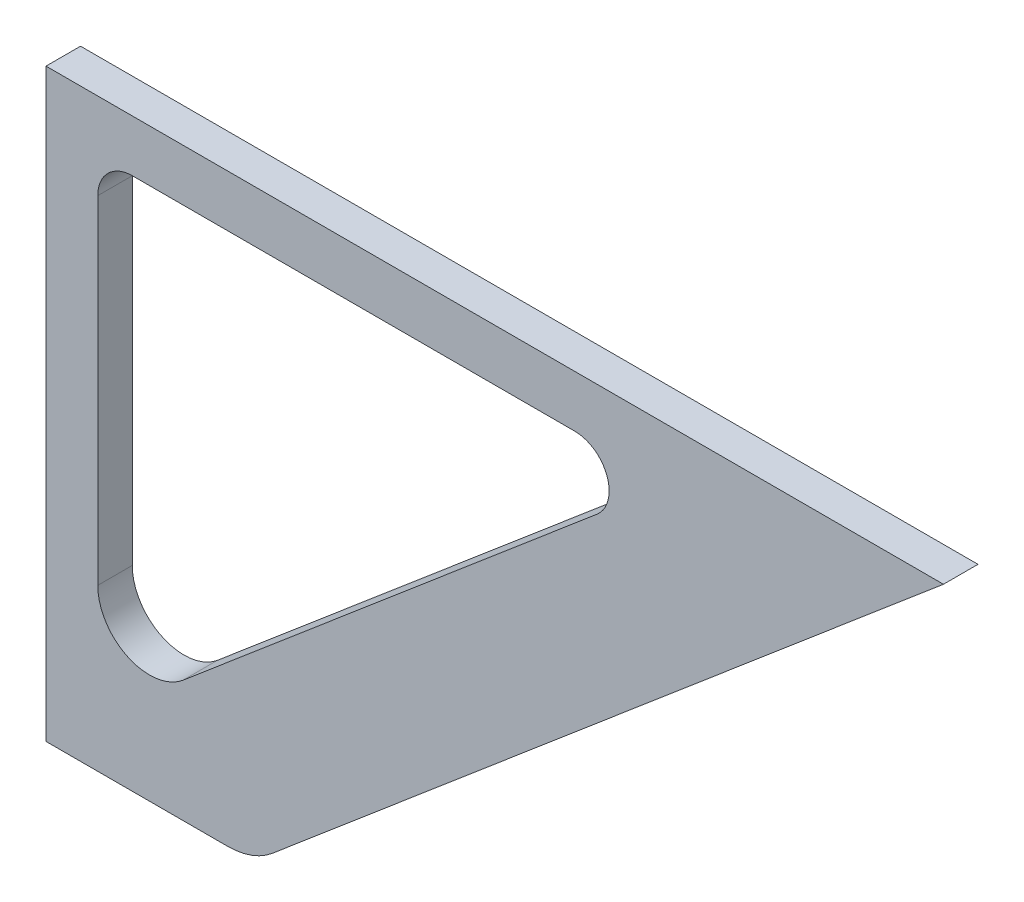
SolidWorks part; units mm, degrees
ref_plane "Front Plane" through (0, 0, 0) normal (0, 0, 1) x (1, 0, 0)
ref_plane "Top Plane" through (0, 0, 0) normal (0, 1, 0) x (1, 0, 0)
ref_plane "Right Plane" through (0, 0, 0) normal (1, 0, 0) x (0, 0, -1)
sketch "Sketch1" plane through (0, 0, 0) normal (0, 0, 1) x (1, 0, 0)
  line L0 (0, 0) -> (0, -53.7972)
  line L1 (0, -53.7972) -> (16.7218, -53.7972)
  line L2 (20.8264, -52.2922) -> (82.55, 0)
  line L3 (7.9375, -4.7625) -> (48.6221, -4.7625)
  line L4 (82.55, 0) -> (0, 0)
  line L5 (50.6744, -10.36) -> (12.6035, -42.6137)
  line L6 (4.7625, -38.9799) -> (4.7625, -7.9375)
  arc A0 (16.7218, -53.7972) -> (20.8264, -52.2922) centre (16.7218, -47.4472) ccw
  arc A1 (7.9375, -4.7625) -> (4.7625, -7.9375) centre (7.9375, -7.9375) ccw
  arc A2 (12.6035, -42.6137) -> (4.7625, -38.9799) centre (9.525, -38.9799) cw
  arc A3 (48.6221, -4.7625) -> (50.6744, -10.36) centre (48.6221, -7.9375) cw
  point P7 (19.05, -53.7972)
  dimension "D4" = 6.35
  dimension "D8" = 4.7625
  dimension "D9" = 3.175
  dimension "D1" = 53.7972
  dimension "D2" = 19.05
  dimension "D3" = 82.55
  dimension "D5" = 12.7
  dimension "D6" = 4.7625
  dimension "D7" = 4.7625
extrude "Boss-Extrude1" add sketch "Sketch1" along normal blind 3.175
